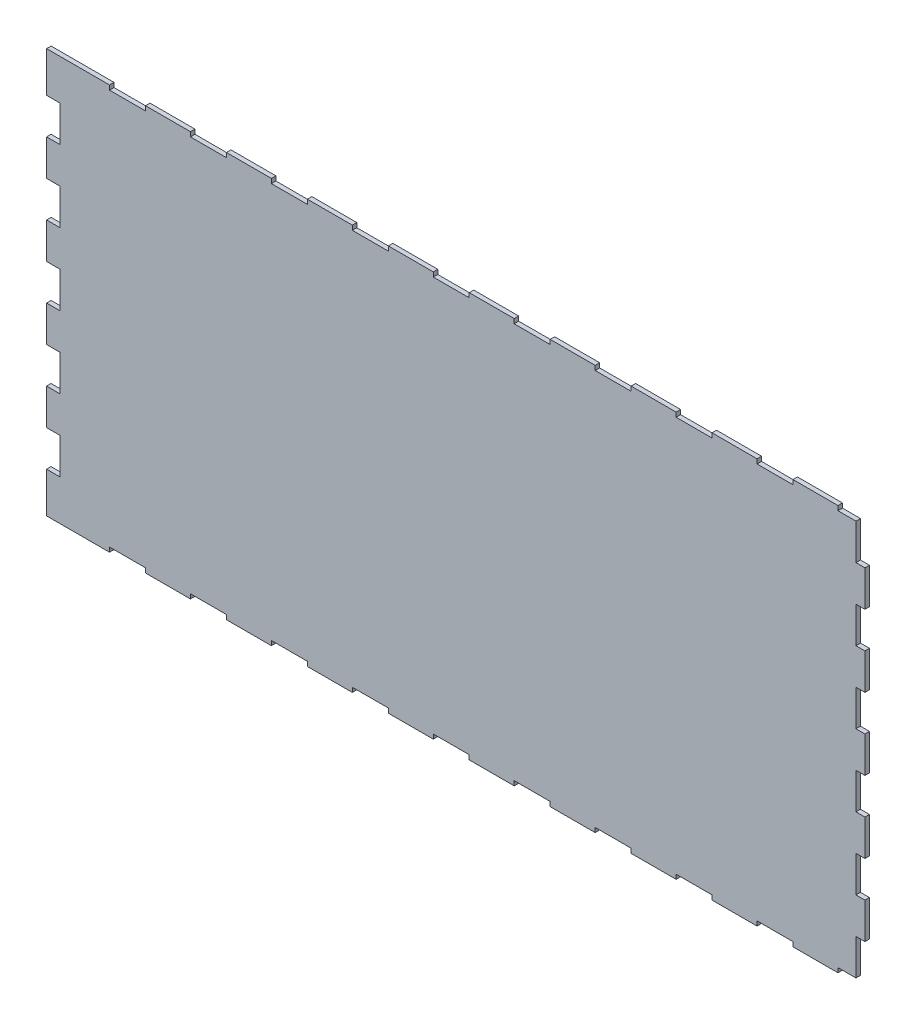
SolidWorks part; units mm, degrees
ref_plane "Front Plane" through (0, 0, 0) normal (0, 0, 1) x (1, 0, 0)
ref_plane "Top Plane" through (0, 0, 0) normal (0, 1, 0) x (1, 0, 0)
ref_plane "Right Plane" through (0, 0, 0) normal (1, 0, 0) x (0, 0, -1)
sketch "Sketch1" plane through (0, 0, 0) normal (0, 0, 1) x (1, 0, 0)
  line L0 (885, 100) -> (885, 60)
  line L1 (-900, 225) -> (-830, 225)
  line L2 (-900, 225) -> (-900, 180)
  line L4 (900, 225) -> (900, 180)
  line L5 (-900, 225) -> (900, -225) construction
  line L6 (-900, -225) -> (900, 225) construction
  line L7 (900, 180) -> (885, 180)
  line L9 (900, 140) -> (885, 140)
  line L10 (885, 180) -> (885, 140)
  line L11 (900, 100) -> (885, 100)
  line L12 (900, 60) -> (885, 60)
  line L13 (885, 20) -> (885, -20)
  line L14 (900, 20) -> (885, 20)
  line L15 (900, -20) -> (885, -20)
  line L16 (885, -60) -> (885, -100)
  line L17 (900, -60) -> (885, -60)
  line L18 (900, -100) -> (885, -100)
  line L19 (885, -140) -> (885, -180)
  line L20 (900, -140) -> (885, -140)
  line L21 (900, -180) -> (885, -180)
  line L22 (900, 60) -> (900, 20)
  line L23 (900, -20) -> (900, -60)
  line L24 (900, -100) -> (900, -140)
  line L25 (900, -180) -> (900, -225)
  line L26 (900, 140) -> (900, 100)
  line L27 (0, -1000) -> (0, -180) construction
  line L28 (-900, -180) -> (-885, -180)
  line L29 (-900, -140) -> (-885, -140)
  line L30 (-885, -140) -> (-885, -180)
  line L31 (-900, -100) -> (-885, -100)
  line L32 (-900, -60) -> (-885, -60)
  line L33 (-885, -60) -> (-885, -100)
  line L34 (-900, -20) -> (-885, -20)
  line L35 (-900, 20) -> (-885, 20)
  line L36 (-885, 20) -> (-885, -20)
  line L37 (-900, 60) -> (-885, 60)
  line L38 (-900, 100) -> (-885, 100)
  line L39 (-885, 180) -> (-885, 140)
  line L40 (-900, 140) -> (-885, 140)
  line L41 (-900, 180) -> (-885, 180)
  line L42 (-885, 100) -> (-885, 60)
  line L43 (-900, 140) -> (-900, 100)
  line L44 (-900, 60) -> (-900, 20)
  line L45 (-900, -20) -> (-900, -60)
  line L46 (-900, -100) -> (-900, -140)
  line L47 (-900, -180) -> (-900, -225)
  line L48 (-790, -225) -> (-740, -225)
  line L49 (790, 225) -> (790, 220) construction
  line L50 (790, 220) -> (830, 220) construction
  line L51 (830, 220) -> (830, 225) construction
  line L52 (-700, -225) -> (-650, -225)
  line L53 (700, 225) -> (700, 220) construction
  line L54 (700, 220) -> (740, 220) construction
  line L55 (740, 220) -> (740, 225) construction
  line L56 (-610, -225) -> (-560, -225)
  line L57 (610, 225) -> (610, 220) construction
  line L58 (610, 220) -> (650, 220) construction
  line L59 (650, 220) -> (650, 225) construction
  line L60 (-520, -225) -> (-470, -225)
  line L61 (520, 225) -> (520, 220) construction
  line L62 (520, 220) -> (560, 220) construction
  line L63 (560, 220) -> (560, 225) construction
  line L64 (-430, -225) -> (-380, -225)
  line L65 (430, 225) -> (430, 220) construction
  line L66 (430, 220) -> (470, 220) construction
  line L67 (470, 220) -> (470, 225) construction
  line L68 (-340, -225) -> (-290, -225)
  line L69 (340, 225) -> (340, 220) construction
  line L70 (340, 220) -> (380, 220) construction
  line L71 (380, 220) -> (380, 225) construction
  line L72 (-250, -225) -> (-200, -225)
  line L73 (250, 225) -> (250, 220) construction
  line L74 (250, 220) -> (290, 220) construction
  line L75 (290, 220) -> (290, 225) construction
  line L76 (-160, -225) -> (-110, -225)
  line L77 (160, 225) -> (160, 220) construction
  line L78 (160, 220) -> (200, 220) construction
  line L79 (200, 220) -> (200, 225) construction
  line L80 (-70, -225) -> (-20, -225)
  line L81 (70, 225) -> (70, 220) construction
  line L82 (70, 220) -> (110, 220) construction
  line L83 (110, 220) -> (110, 225) construction
  line L84 (20, -225) -> (70, -225)
  line L85 (-20, 225) -> (-20, 220) construction
  line L86 (-20, 220) -> (20, 220) construction
  line L87 (20, 220) -> (20, 225) construction
  line L88 (110, -225) -> (160, -225)
  line L89 (-110, 225) -> (-110, 220) construction
  line L90 (-110, 220) -> (-70, 220) construction
  line L91 (-70, 220) -> (-70, 225) construction
  line L92 (200, -225) -> (250, -225)
  line L93 (-200, 225) -> (-200, 220) construction
  line L94 (-200, 220) -> (-160, 220) construction
  line L95 (-160, 220) -> (-160, 225) construction
  line L96 (290, -225) -> (340, -225)
  line L97 (-290, 225) -> (-290, 220) construction
  line L98 (-290, 220) -> (-250, 220) construction
  line L99 (-250, 220) -> (-250, 225) construction
  line L100 (380, -225) -> (430, -225)
  line L101 (-380, 225) -> (-380, 220) construction
  line L102 (-380, 220) -> (-340, 220) construction
  line L103 (-340, 220) -> (-340, 225) construction
  line L104 (470, -225) -> (520, -225)
  line L105 (-470, 225) -> (-470, 220) construction
  line L106 (-470, 220) -> (-430, 220) construction
  line L107 (-430, 220) -> (-430, 225) construction
  line L108 (560, -225) -> (610, -225)
  line L109 (-560, 225) -> (-560, 220) construction
  line L110 (-560, 220) -> (-520, 220) construction
  line L111 (-520, 220) -> (-520, 225) construction
  line L112 (650, -225) -> (700, -225)
  line L113 (-650, 225) -> (-650, 220) construction
  line L114 (-650, 220) -> (-610, 220) construction
  line L115 (-610, 220) -> (-610, 225) construction
  line L116 (740, -225) -> (790, -225)
  line L117 (-740, 225) -> (-740, 220) construction
  line L118 (-740, 220) -> (-700, 220) construction
  line L119 (-700, 220) -> (-700, 225) construction
  line L120 (830, -225) -> (900, -225)
  line L121 (-830, 225) -> (-830, 220) construction
  line L122 (-830, 220) -> (-790, 220) construction
  line L123 (-790, 220) -> (-790, 225) construction
  line L125 (790, 225) -> (790, 220)
  line L126 (790, 220) -> (830, 220)
  line L127 (830, 220) -> (830, 225)
  line L129 (700, 225) -> (700, 220)
  line L130 (700, 220) -> (740, 220)
  line L131 (740, 220) -> (740, 225)
  line L133 (610, 225) -> (610, 220)
  line L134 (610, 220) -> (650, 220)
  line L135 (650, 220) -> (650, 225)
  line L137 (520, 225) -> (520, 220)
  line L138 (520, 220) -> (560, 220)
  line L139 (560, 220) -> (560, 225)
  line L141 (430, 225) -> (430, 220)
  line L142 (430, 220) -> (470, 220)
  line L143 (470, 220) -> (470, 225)
  line L145 (340, 225) -> (340, 220)
  line L146 (340, 220) -> (380, 220)
  line L147 (380, 220) -> (380, 225)
  line L149 (250, 225) -> (250, 220)
  line L150 (250, 220) -> (290, 220)
  line L151 (290, 220) -> (290, 225)
  line L153 (160, 225) -> (160, 220)
  line L154 (160, 220) -> (200, 220)
  line L155 (200, 220) -> (200, 225)
  line L157 (70, 225) -> (70, 220)
  line L158 (70, 220) -> (110, 220)
  line L159 (110, 220) -> (110, 225)
  line L161 (-20, 225) -> (-20, 220)
  line L162 (-20, 220) -> (20, 220)
  line L163 (20, 220) -> (20, 225)
  line L165 (-110, 225) -> (-110, 220)
  line L166 (-110, 220) -> (-70, 220)
  line L167 (-70, 220) -> (-70, 225)
  line L169 (-200, 225) -> (-200, 220)
  line L170 (-200, 220) -> (-160, 220)
  line L171 (-160, 220) -> (-160, 225)
  line L173 (-290, 225) -> (-290, 220)
  line L174 (-290, 220) -> (-250, 220)
  line L175 (-250, 220) -> (-250, 225)
  line L177 (-380, 225) -> (-380, 220)
  line L178 (-380, 220) -> (-340, 220)
  line L179 (-340, 220) -> (-340, 225)
  line L181 (-470, 225) -> (-470, 220)
  line L182 (-470, 220) -> (-430, 220)
  line L183 (-430, 220) -> (-430, 225)
  line L185 (-560, 225) -> (-560, 220)
  line L186 (-560, 220) -> (-520, 220)
  line L187 (-520, 220) -> (-520, 225)
  line L189 (-650, 225) -> (-650, 220)
  line L190 (-650, 220) -> (-610, 220)
  line L191 (-610, 220) -> (-610, 225)
  line L193 (-740, 225) -> (-740, 220)
  line L194 (-740, 220) -> (-700, 220)
  line L195 (-700, 220) -> (-700, 225)
  line L197 (-830, 225) -> (-830, 220)
  line L198 (-830, 220) -> (-790, 220)
  line L199 (-790, 220) -> (-790, 225)
  line L200 (830, 225) -> (900, 225)
  line L201 (740, 225) -> (790, 225)
  line L202 (650, 225) -> (700, 225)
  line L203 (560, 225) -> (610, 225)
  line L204 (470, 225) -> (520, 225)
  line L205 (380, 225) -> (430, 225)
  line L206 (290, 225) -> (340, 225)
  line L207 (200, 225) -> (250, 225)
  line L208 (110, 225) -> (160, 225)
  line L209 (20, 225) -> (70, 225)
  line L210 (-70, 225) -> (-20, 225)
  line L211 (-160, 225) -> (-110, 225)
  line L212 (-250, 225) -> (-200, 225)
  line L213 (-340, 225) -> (-290, 225)
  line L214 (-430, 225) -> (-380, 225)
  line L215 (-520, 225) -> (-470, 225)
  line L216 (-610, 225) -> (-560, 225)
  line L217 (-700, 225) -> (-650, 225)
  line L218 (-790, 225) -> (-740, 225)
  line L219 (0, 0) -> (226.4615, 0) construction
  line L220 (-740, -225) -> (-740, -220)
  line L222 (-830, -225) -> (-830, -220)
  line L223 (-830, -220) -> (-790, -220)
  line L224 (-790, -225) -> (-790, -220)
  line L225 (-700, -225) -> (-700, -220)
  line L226 (-740, -220) -> (-700, -220)
  line L227 (-650, -225) -> (-650, -220)
  line L228 (-610, -225) -> (-610, -220)
  line L229 (-650, -220) -> (-610, -220)
  line L230 (-560, -225) -> (-560, -220)
  line L231 (-520, -225) -> (-520, -220)
  line L232 (-560, -220) -> (-520, -220)
  line L233 (-470, -225) -> (-470, -220)
  line L234 (-430, -225) -> (-430, -220)
  line L235 (-470, -220) -> (-430, -220)
  line L236 (-380, -225) -> (-380, -220)
  line L237 (-340, -225) -> (-340, -220)
  line L238 (-380, -220) -> (-340, -220)
  line L239 (-290, -225) -> (-290, -220)
  line L240 (-250, -225) -> (-250, -220)
  line L241 (-290, -220) -> (-250, -220)
  line L242 (-200, -225) -> (-200, -220)
  line L243 (-160, -225) -> (-160, -220)
  line L244 (-200, -220) -> (-160, -220)
  line L245 (-110, -225) -> (-110, -220)
  line L246 (-70, -225) -> (-70, -220)
  line L247 (-110, -220) -> (-70, -220)
  line L248 (-20, -225) -> (-20, -220)
  line L249 (20, -225) -> (20, -220)
  line L250 (-20, -220) -> (20, -220)
  line L251 (70, -225) -> (70, -220)
  line L252 (110, -225) -> (110, -220)
  line L253 (70, -220) -> (110, -220)
  line L254 (160, -225) -> (160, -220)
  line L255 (200, -225) -> (200, -220)
  line L256 (160, -220) -> (200, -220)
  line L257 (250, -225) -> (250, -220)
  line L258 (290, -225) -> (290, -220)
  line L259 (250, -220) -> (290, -220)
  line L260 (340, -225) -> (340, -220)
  line L261 (380, -225) -> (380, -220)
  line L262 (340, -220) -> (380, -220)
  line L263 (430, -225) -> (430, -220)
  line L264 (470, -225) -> (470, -220)
  line L265 (430, -220) -> (470, -220)
  line L266 (520, -225) -> (520, -220)
  line L267 (560, -225) -> (560, -220)
  line L268 (520, -220) -> (560, -220)
  line L269 (610, -225) -> (610, -220)
  line L270 (650, -225) -> (650, -220)
  line L271 (610, -220) -> (650, -220)
  line L272 (700, -225) -> (700, -220)
  line L273 (740, -225) -> (740, -220)
  line L274 (700, -220) -> (740, -220)
  line L275 (790, -225) -> (790, -220)
  line L276 (830, -225) -> (830, -220)
  line L277 (790, -220) -> (830, -220)
  line L278 (-900, -225) -> (-830, -225)
  line L279 (10, 100) -> (10, 60)
  line L280 (0, 180) -> (10, 180)
  line L282 (0, 140) -> (10, 140)
  line L283 (10, 180) -> (10, 140)
  line L284 (0, 100) -> (10, 100)
  line L285 (0, 60) -> (10, 60)
  line L287 (10, 20) -> (10, -20)
  line L288 (0, 20) -> (10, 20)
  line L289 (0, -20) -> (10, -20)
  line L291 (10, -60) -> (10, -100)
  line L292 (0, -60) -> (10, -60)
  line L293 (0, -100) -> (10, -100)
  line L295 (10, -140) -> (10, -180)
  line L296 (0, -140) -> (10, -140)
  line L297 (0, -180) -> (10, -180)
  line L299 (0, 220) -> (0, 180)
  line L300 (0, 140) -> (0, 100)
  line L301 (0, 180) -> (0, 1220) construction
  line L302 (0, 60) -> (0, 20)
  line L303 (0, 100) -> (0, 140) construction
  line L304 (0, -20) -> (0, -60)
  line L305 (0, 20) -> (0, 60) construction
  line L306 (0, -100) -> (0, -140)
  line L307 (0, -60) -> (0, -20) construction
  line L308 (0, -180) -> (0, -220)
  line L309 (0, -140) -> (0, -100) construction
  point P0 (0, 0)
  point P211 (10, 0)
  dimension "D1" = 40
  dimension "D2" = 70
  dimension "D3" = 15
  dimension "D4" = 40
  dimension "D5" = 40
  dimension "D7" = 19
  dimension "D8" = 10
  dimension "D6" = 5
  dimension "D9" = 5
extrude "Boss-Extrude1" add sketch "Sketch1" along normal blind 5 contours L47 L278 L222 L223 L224 L48 L220 L226 L225 L52 L227 L229 L228 L56 L230 L232 L231 L60 L233 L235 L234 L64 L236 L238 L237 L68 L239 L241 L240 L72 L242 L244 L243 L76 L245 L247 L246 L80 L248 L250 L249 L84 L251 L253 L252 L88 L254 L256 L255 L92 L257
